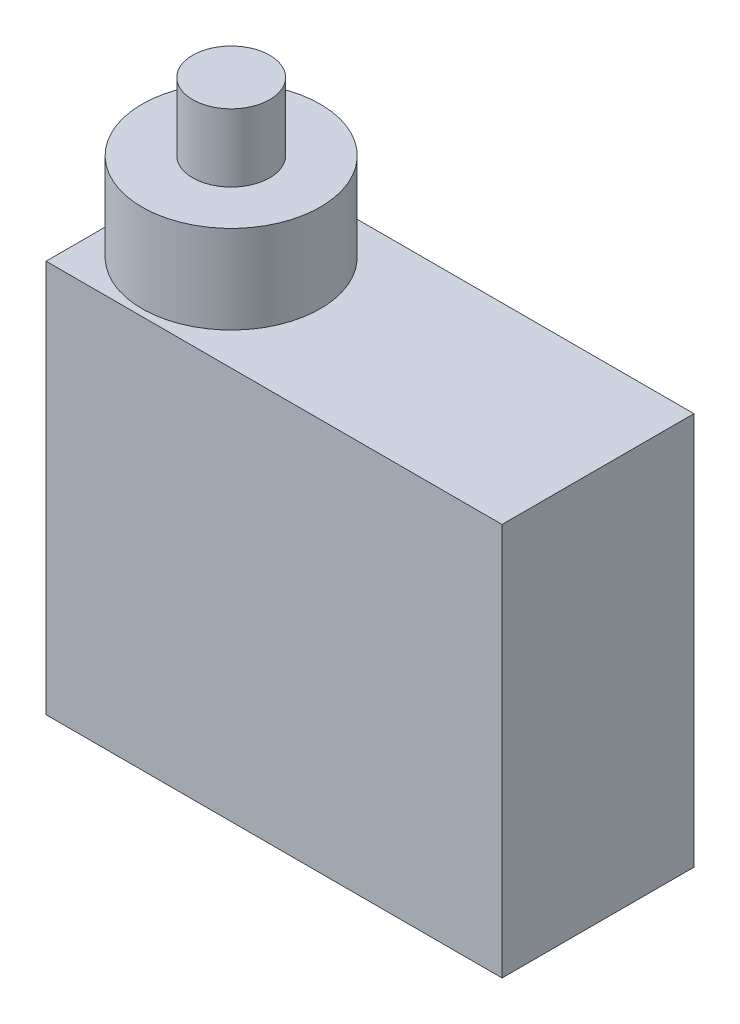
SolidWorks part; units mm, degrees
ref_plane "Front Plane" through (0, 0, 0) normal (0, 0, 1) x (1, 0, 0)
ref_plane "Top Plane" through (0, 0, 0) normal (0, 1, 0) x (1, 0, 0)
ref_plane "Right Plane" through (0, 0, 0) normal (1, 0, 0) x (0, 0, -1)
sketch "Sketch1" plane through (0, 0, 0) normal (0, 0, 1) x (1, 0, 0)
  line L1 (10.1, 8.7) -> (-10.1, 8.7)
  line L2 (10.1, 8.7) -> (10.1, -8.7)
  line L3 (10.1, -8.7) -> (-10.1, -8.7)
  line L4 (-10.1, 8.7) -> (-10.1, -8.7)
  line L5 (10.1, 8.7) -> (-10.1, -8.7) construction
  line L6 (10.1, -8.7) -> (-10.1, 8.7) construction
  point P0 (0, 0)
  dimension "D1" = 17.4
  dimension "D2" = 20.2
extrude "Boss-Extrude1" add sketch "Sketch1" along normal blind 8.5
sketch "Sketch2" plane through (0, 8.7, 0) normal (0, 1, 0) x (1, 0, 0)
  line L0 (-10.1, -4.25) -> (10.1, -4.25) construction
  line L1 (-10.1, -8.5) -> (-10.1, 0) construction
  line L2 (10.1, -8.5) -> (10.1, 0) construction
  circle A0 centre (-6.15, -4.25) radius 3.95
  dimension "D2" = 7.9
  dimension "D1" = 3.95
extrude "Boss-Extrude2" add sketch "Sketch2" along normal blind 3.9
sketch "Sketch3" plane through (0, 12.6, 0) normal (0, 1, 0) x (1, 0, 0)
  line L0 (-10.1, -4.25) -> (-6.15, -4.25) construction
  circle A1 centre (-6.15, -4.25) radius 1.7065
  dimension "D1" = 3.413
extrude "Boss-Extrude3" add sketch "Sketch3" along normal blind 3
